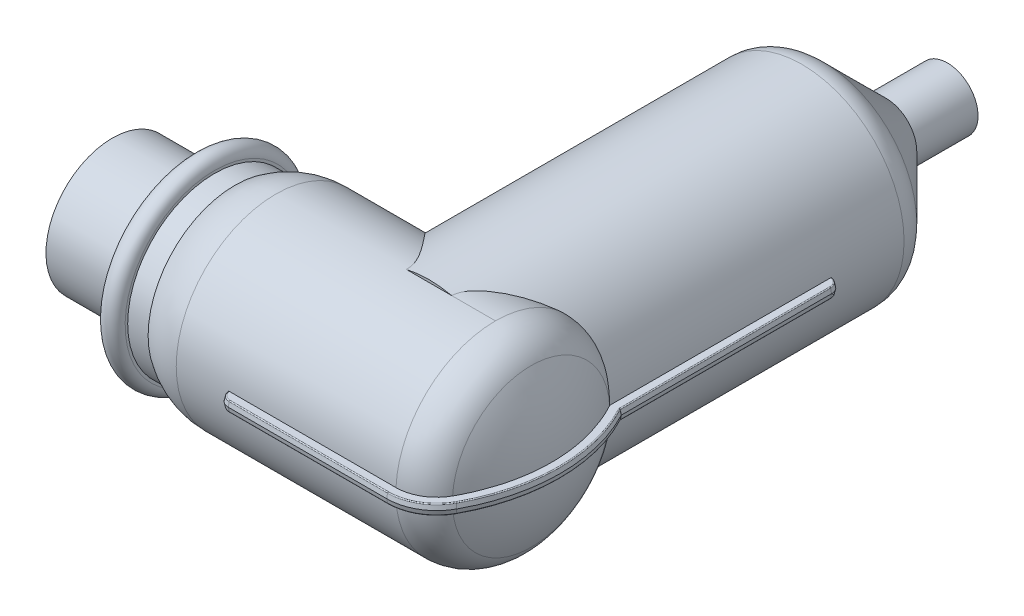
SolidWorks part; units mm, degrees
ref_plane "Front Plane" through (0, 0, 0) normal (0, 0, 1) x (1, 0, 0)
ref_plane "Top Plane" through (0, 0, 0) normal (0, 1, 0) x (1, 0, 0)
ref_plane "Right Plane" through (0, 0, 0) normal (1, 0, 0) x (0, 0, -1)
sketch "Sketch1" plane through (0, 0, 0) normal (0, 0, 1) x (1, 0, 0)
  line L0 (8, 6.5) -> (8, 8.75)
  line L2 (10, 8.75) -> (10, 8.5)
  line L3 (10, 8.5) -> (12, 8.5)
  line L4 (0, 0) -> (43, 0)
  line L5 (37.5, 9.75) -> (16, 9.75)
  line L6 (0, 0) -> (-5.7927, 0) construction
  line L7 (43, 0) -> (43, 7.3633) construction
  line L8 (8, 6.5) -> (0, 6.5)
  line L9 (0, 6.5) -> (0, 0)
  arc A0 (8, 8.75) -> (10, 8.75) centre (9, 8.75) cw
  arc A1 (16, 9.75) -> (12, 8.5) centre (16, 2.725) ccw
  arc A2 (43, 0) -> (40.9903, 7.704) centre (27.2292, 0) ccw
  arc A3 (37.5, 9.75) -> (40.9903, 7.704) centre (37.5, 5.75) cw
  dimension "D9" = 4
  dimension "D1" = 2
  dimension "D2" = 17.5
  dimension "D3" = 4
  dimension "D4" = 8
  dimension "D5" = 17
  dimension "D6" = 35
  dimension "D7" = 29.5
  dimension "D8" = 19.5
  dimension "D10" = 13
  dimension "D11" = 8
revolve "Revolve1" add sketch "Sketch1" angle 360 about L6
sketch "Sketch2" plane through (0, 0, 0) normal (0, 1, 0) x (1, 0, 0)
  line L0 (31, 0) -> (31, -17.9723) construction
  line L1 (31, 0) -> (0, 0) construction
  line L2 (41, 0) -> (31, 0)
  line L3 (31, 0) -> (31, 50.7426)
  line L4 (31, 50.7426) -> (34, 50.7426)
  line L5 (34, 50.7426) -> (34, 44.7426)
  line L6 (34, 44.7426) -> (40.1213, 38.6213)
  line L7 (41, 36.5) -> (41, 0)
  arc A0 (40.1213, 38.6213) -> (41, 36.5) centre (38, 36.5) cw
  dimension "D6" = 6
  dimension "D5" = 3
  dimension "D1" = 31
  dimension "D2" = 45
  dimension "D3" = 36.5
  dimension "D4" = 20
  dimension "D8" = 6
revolve "Revolve2" add sketch "Sketch2" angle 360 about L0
sketch "Sketch3" plane through (0, 0, 0) normal (0, 1, 0) x (1, 0, 0)
  line L0 (37.5, 6.1084) -> (37.5, -9.75) construction
  line L1 (40.9, 7.661) -> (40.9, 29.5)
  line L2 (0, 0) -> (43, 0) construction
  line L3 (21, -9.65) -> (37.5, -9.65)
  line L4 (31, 0) -> (31, 50.7426) construction
  line L5 (21.1, 9.65) -> (18, 9.65)
  line L7 (21.1, 29.5) -> (21.1, 9.65)
  line L8 (21, 36.5) -> (41, 36.5) construction
  line L9 (16, -9.75) -> (16, 9.75) construction
  line L10 (22, -10.65) -> (37.5, -10.65)
  line L11 (41.9, 7.9136) -> (41.9, 28.5)
  line L12 (20.1, 28.5) -> (20.1, 10.65)
  line L13 (20.1, 10.65) -> (19, 10.65)
  line L14 (41.9, 7.9136) -> (41.9, 29.5) construction
  line L15 (20.1, 29.5) -> (20.1, 10.65) construction
  line L16 (20.1, 10.65) -> (18, 10.65) construction
  line L17 (21, -10.65) -> (37.5, -10.65) construction
  line L18 (31, 0) -> (0, 0) construction
  arc A0 (40.9231, -7.6187) -> (40.9, 7.661) centre (26.9673, 0) ccw construction
  arc A1 (40.9231, -7.6187) -> (40.9, 7.661) centre (26.9673, 0) ccw
  arc A3 (37.5, -9.65) -> (40.9231, -7.6187) centre (37.5, -5.75) ccw
  arc A4 (37.5, -10.65) -> (41.8008, -8.0979) centre (37.5, -5.75) ccw
  arc A5 (41.8008, -8.0979) -> (41.9, 7.9136) centre (26.9673, 0) ccw
  arc A6 (41.9, 28.5) -> (40.9, 29.5) centre (40.9, 28.5) ccw
  arc A7 (20.1, 28.5) -> (21.1, 29.5) centre (21.1, 28.5) cw
  arc A8 (19, 10.65) -> (18, 9.65) centre (19, 9.65) ccw
  arc A9 (22, -10.65) -> (21, -9.65) centre (22, -9.65) cw
  dimension "D11" = 3.9
  dimension "D12" = 15.9
  dimension "D1" = 7
  dimension "D2" = 7
  dimension "D3" = 2
  dimension "D4" = 5
  dimension "D7" = 9.9
  dimension "D8" = 9.65
  dimension "D9" = 9.9
  dimension "D10" = 9.65
  dimension "D5" = 1
  dimension "D6" = 1
extrude "Boss-Extrude1" add sketch "Sketch3" along normal mid plane 1 draft 12
fillet "Fillet1" radius 0.1 24 edges at (20.4315, 0.5, -29.0932) (20.4315, -0.5, -29.0932) (20.2063, 0.5, -19.5219) (20.2063, -0.5, -19.5219) (18.4068, -0.5, -10.3185) (19.6031, 0.5, -10.5437) (41.5685, 0.5, -29.0932) (21.4068, 0.5, 10.3185) (29.75, 0.5, 10.5437) (39.9463, 0.5, 9.8726) (41.5685, -0.5, -29.0932) (43.7608, -0.5, 0.0908) (39.9463, -0.5, 9.8726) (29.75, -0.5, 10.5437) (19.6031, -0.5, -10.5437) (20.1531, -0.25, -10.5969) (20.1531, 0.25, -10.5969) (18.4068, 0.5, -10.3185) (41.7937, 0.5, -18.1936) (43.7608, 0.5, 0.0908) (41.7937, -0.5, -18.1936) (21.4068, -0.5, 10.3185)
